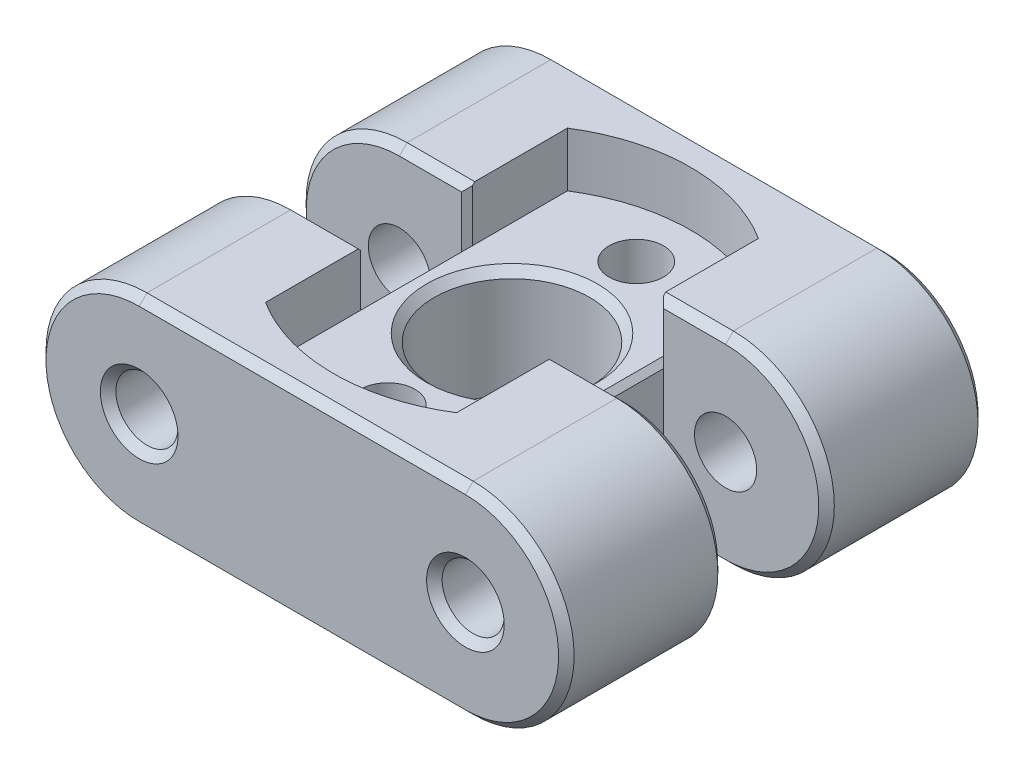
SolidWorks part; units mm, degrees
ref_plane "Front Plane" through (0, 0, 0) normal (0, 0, 1) x (1, 0, 0)
ref_plane "Top Plane" through (0, 0, 0) normal (0, 1, 0) x (1, 0, 0)
ref_plane "Right Plane" through (0, 0, 0) normal (1, 0, 0) x (0, 0, -1)
sketch "Sketch1" plane through (0, 0, 0) normal (0, 1, 0) x (1, 0, 0)
  line L1 (-10.5, -13.5) -> (10.5, -13.5)
  line L2 (-10.5, -13.5) -> (-10.5, 13.5)
  line L3 (-10.5, 13.5) -> (10.5, 13.5)
  line L4 (10.5, -13.5) -> (10.5, 13.5)
  line L5 (-10.5, -13.5) -> (10.5, 13.5) construction
  line L6 (-10.5, 13.5) -> (10.5, -13.5) construction
  point P0 (0, 0)
  dimension "D1" = 27
  dimension "D2" = 21
extrude "Boss-Extrude1" add sketch "Sketch1" along normal blind 13
sketch "Sketch8" plane through (0, 0, -13.5) normal (0, 0, -1) x (-1, 0, 0)
  line L0 (-10.5, 13) -> (-10.5, 0) construction
  line L1 (10.5, 13) -> (10.5, 0) construction
  circle A0 centre (-10.5, 6.5) radius 6.5
  circle A1 centre (10.5, 6.5) radius 6.5
extrude "Boss-Extrude2" add sketch "Sketch8" against normal up to surface (27 mm away) up to face at (0, 6.5, 13.5)
sketch "Sketch2" plane through (0, 13, 0) normal (0, 1, 0) x (1, 0, 0)
  circle A0 centre (0, 0) radius 5
  dimension "D1" = 10
extrude "Cut-Extrude1" cut sketch "Sketch2" against normal blind 13
sketch "Sketch3" plane through (0, 13, 0) normal (0, 1, 0) x (1, 0, 0)
  line L1 (6.5, 3.25) -> (28.0017, 3.25)
  line L2 (6.5, 3.25) -> (6.5, -3.25)
  line L3 (6.5, -3.25) -> (28.0017, -3.25)
  line L4 (28.0017, 3.25) -> (28.0017, -3.25)
  line L5 (6.5, 3.25) -> (28.0017, -3.25) construction
  line L6 (6.5, -3.25) -> (28.0017, 3.25) construction
  line L7 (-6.5, 0) -> (6.5, 0) construction
  line L8 (0, 0) -> (0, 13.5) construction
  line L9 (10.5, 13.5) -> (-10.5, 13.5) construction
  line L10 (-6.5, -3.25) -> (-28.0017, 3.25) construction
  line L11 (-6.5, 3.25) -> (-28.0017, -3.25) construction
  line L12 (-28.0017, 3.25) -> (-28.0017, -3.25)
  line L13 (-6.5, -3.25) -> (-28.0017, -3.25)
  line L14 (-6.5, 3.25) -> (-6.5, -3.25)
  line L15 (-6.5, 3.25) -> (-28.0017, 3.25)
  point P0 (17.2509, 0)
  point P18 (-17.2509, 0)
  dimension "D1" = 13
  dimension "D2" = 6.5
extrude "Cut-Extrude2" cut sketch "Sketch3" against normal blind 13
sketch "Sketch7" plane through (0, 13, 0) normal (0, 1, 0) x (1, 0, 0)
  line L1 (-6.5, -3.25) -> (6.5, -3.25)
  line L2 (-6.5, -3.25) -> (-6.5, 3.25)
  line L3 (-6.5, 3.25) -> (6.5, 3.25)
  line L4 (6.5, -3.25) -> (6.5, 3.25)
  line L5 (-6.5, -3.25) -> (6.5, 3.25) construction
  line L6 (-6.5, 3.25) -> (6.5, -3.25) construction
  point P0 (0, 0)
extrude "Cut-Extrude7" cut sketch "Sketch7" against normal blind 3.5
sketch "Sketch4" plane through (0, 0, 13.5) normal (0, 0, 1) x (1, 0, 0)
  line L0 (-10.5, 6.5) -> (0, 6.5) construction
  line L1 (0, 6.5) -> (0, 0) construction
  line L2 (0, 6.5) -> (10.5, 6.5) construction
  line L3 (0, 6.5) -> (0, 13) construction
  line L4 (-10.5, 13) -> (10.5, 13) construction
  circle A0 centre (-10.5, 6.5) radius 2
  circle A1 centre (10.5, 6.5) radius 2
  dimension "D2" = 4
  dimension "D1" = 21
extrude "Cut-Extrude3" cut sketch "Sketch4" against normal blind 35
sketch "Sketch5" plane through (0, 13, 0) normal (0, 1, 0) x (1, 0, 0)
  line L2 (-6.15, 9.7174) -> (-6.15, -9.7174)
  line L4 (6.15, 9.7174) -> (6.15, -9.7174)
  line L5 (-6.15, 9.7174) -> (6.15, -9.7174) construction
  line L6 (-6.15, -9.7174) -> (6.15, 9.7174) construction
  arc A0 (6.15, 9.7174) -> (-6.15, 9.7174) centre (0, 0) ccw
  arc A1 (-6.15, -9.7174) -> (6.15, -9.7174) centre (0, 0) ccw
  dimension "D1" = 23
  dimension "D2" = 12.3
extrude "Cut-Extrude4" cut sketch "Sketch5" against normal blind 3.5
sketch "Sketch6" plane through (0, 9.5, 0) normal (0, 1, 0) x (1, 0, 0)
  line L0 (0, -8) -> (0, 8) construction
  circle A0 centre (0, 8) radius 1.75
  circle A1 centre (0, -8) radius 1.75
  point P5 (0, 0)
  dimension "D1" = 3.5
  dimension "D2" = 16
extrude "Cut-Extrude5" cut sketch "Sketch6" against normal blind 6
chamfer "Chamfer1" distance 0.5 angle 45 26 edges at (12.5, 6.5, 13.5) (-8.5, 6.5, 13.5) (12.5, 6.5, -13.5) (-8.5, 6.5, -13.5) (0, 13, 13.5) (0, 0, 13.5) (0, 13, -13.5) (8.325, 13, -3.25) (8.325, 13, 3.25) (8.5, 0, 3.25) (8.5, 0, -3.25) (0, 0, -13.5) (-8.5, 0, 3.25) (-8.5, 0, -3.25) (-8.325, 13, 3.25) (-8.325, 13, -3.25) (0, 0, 5) (0, 9.5, -5) (17, 6.5, 13.5) (-17, 6.5, 13.5) (17, 6.5, -3.25) (17, 6.5, -13.5) (17, 6.5, 3.25) (-17, 6.5, -3.25) (-17, 6.5, -13.5) (-17, 6.5, 3.25)
chamfer "Chamfer2" distance 0.35 angle 45 4 edges at (6.15, 11, 3.25) (6.15, 11, -3.25) (-6.15, 11, -3.25) (-6.15, 11, 3.25)
chamfer "Chamfer3" distance 0.35 angle 45 4 edges at (6.5, 9.5, 0) (-6.5, 9.5, 0) (-6.5, 0, 0) (6.5, 0, 0)
sketch "Sketch9" plane through (0, 0, 0) normal (0, -1, 0) x (1, 0, 0)
  circle A0 centre (0, 0) radius 10
  dimension "D1" = 20
extrude "Cut-Extrude8" cut sketch "Sketch9" against normal blind 2.5
sketch "Sketch10" plane through (0, 2.5, 0) normal (0, -1, 0) x (1, 0, 0)
  circle A0 centre (0, 0) radius 8
  dimension "D1" = 16
